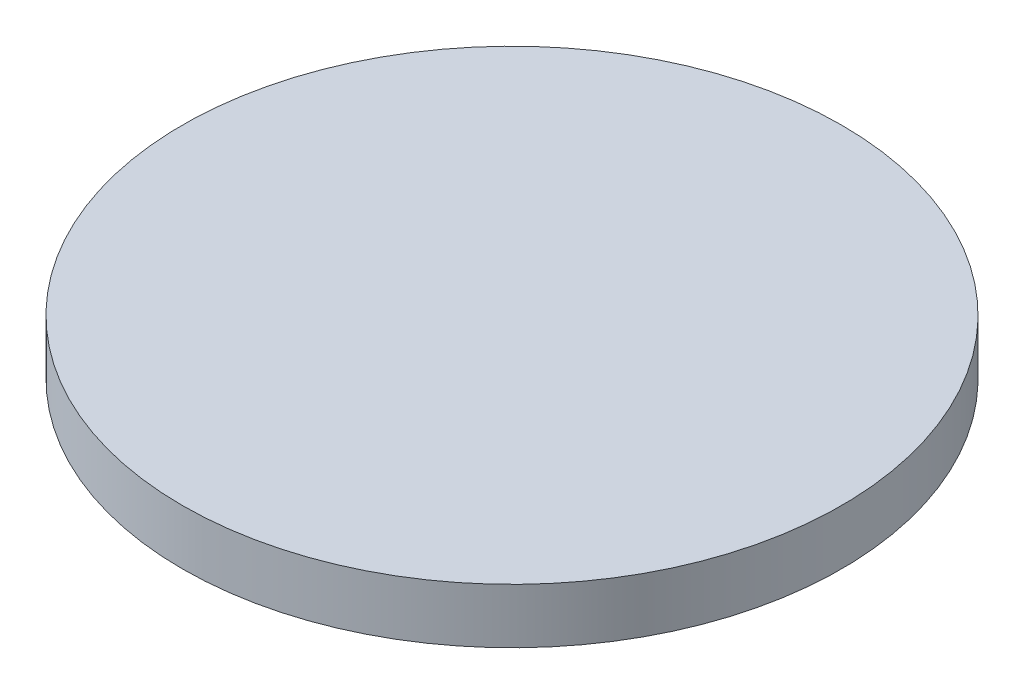
SolidWorks part; units mm, degrees
ref_plane "Front Plane" through (0, 0, 0) normal (0, 0, 1) x (1, 0, 0)
ref_plane "Top Plane" through (0, 0, 0) normal (0, 1, 0) x (1, 0, 0)
ref_plane "Right Plane" through (0, 0, 0) normal (1, 0, 0) x (0, 0, -1)
sketch "Sketch1" plane through (0, 0, 0) normal (0, 1, 0) x (1, 0, 0)
  circle A0 centre (0, 0) radius 76.2
  dimension "D1" = 152.4
extrude "Boss-Extrude1" add sketch "Sketch1" along normal blind 12.7
